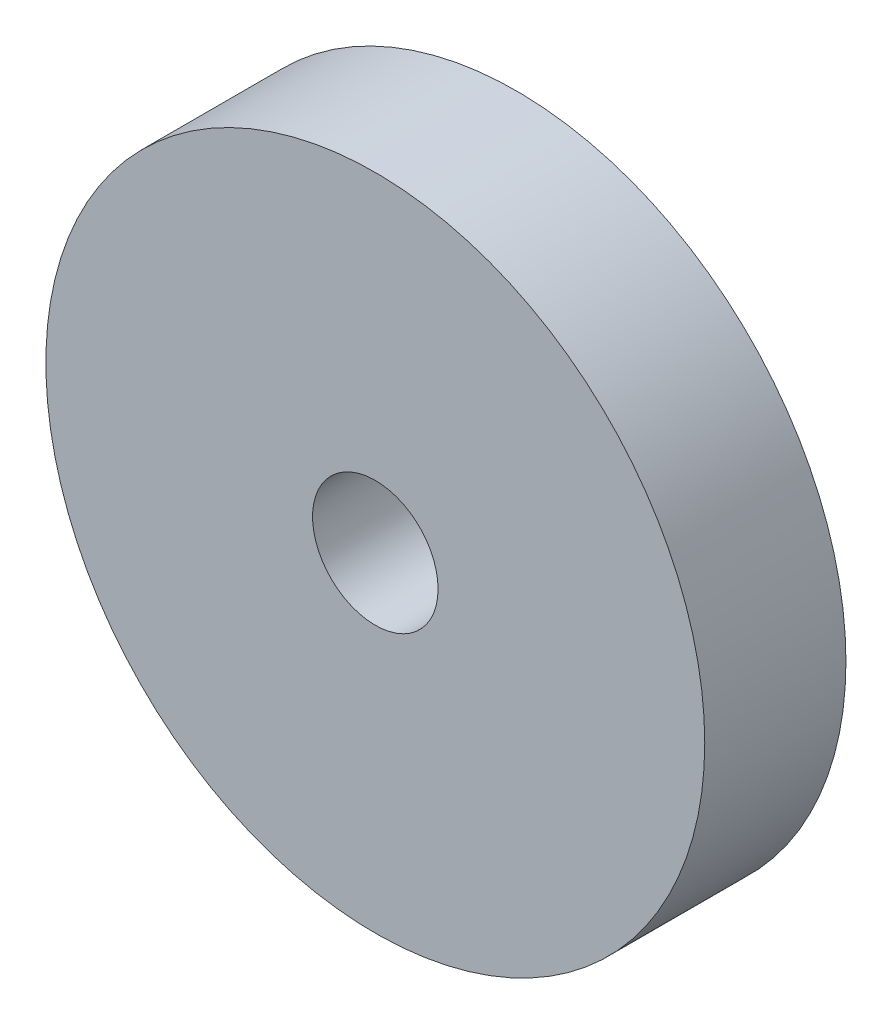
SolidWorks part; units mm, degrees
ref_plane "前视基准面" through (0, 0, 0) normal (0, 0, 1) x (1, 0, 0)
ref_plane "上视基准面" through (0, 0, 0) normal (0, 1, 0) x (1, 0, 0)
ref_plane "右视基准面" through (0, 0, 0) normal (1, 0, 0) x (0, 0, -1)
other "Configuration Table"
sketch "草图1" plane through (0, 0, 0) normal (0, 0, 1) x (1, 0, 0)
  circle A0 centre (0, 0) radius 42
  circle A1 centre (0, 0) radius 8
extrude "凸台-拉伸1" add sketch "草图1" along normal blind 18
sketch "草图2" plane through (0, 0, 0) normal (0, 0, 1) x (1, 0, 0)
  line L0 (37.445, 2.0305) -> (37.5326, 2.0353)
  line L1 (37.5326, 2.0353) -> (37.6055, 2.0362)
  line L2 (37.6055, 2.0362) -> (37.8243, 2.0269)
  line L3 (37.8243, 2.0269) -> (38.1872, 1.9891)
  line L4 (38.1872, 1.9891) -> (38.6911, 1.905)
  line L5 (38.6911, 1.905) -> (39.3309, 1.7569)
  line L6 (39.3309, 1.7569) -> (40.1003, 1.5277)
  line L7 (40.1003, 1.5277) -> (40.9909, 1.2009)
  line L8 (40.9909, 1.2009) -> (41.9931, 0.7606)
  line L9 (41.9931, 0.7606) -> (41.9983, 0.3803)
  line L10 (41.9983, 0.3803) -> (42, 0)
  line L11 (42, 0) -> (41.9983, -0.3803)
  line L12 (41.9983, -0.3803) -> (41.9931, -0.7606)
  line L13 (41.9931, -0.7606) -> (40.9909, -1.2009)
  line L14 (40.9909, -1.2009) -> (40.1003, -1.5277)
  line L15 (40.1003, -1.5277) -> (39.3309, -1.7569)
  line L16 (39.3309, -1.7569) -> (38.6911, -1.905)
  line L17 (38.6911, -1.905) -> (38.1872, -1.9891)
  line L18 (38.1872, -1.9891) -> (37.8243, -2.0269)
  line L19 (37.8243, -2.0269) -> (37.445, -2.0305)
  line L20 (37.445, -2.0305) -> (37.5326, -2.0353)
  line L21 (37.5326, -2.0353) -> (37.445, -2.0305)
  arc A0 (37.445, -2.0305) -> (37.445, 2.0305) centre (0, 0) ccw
